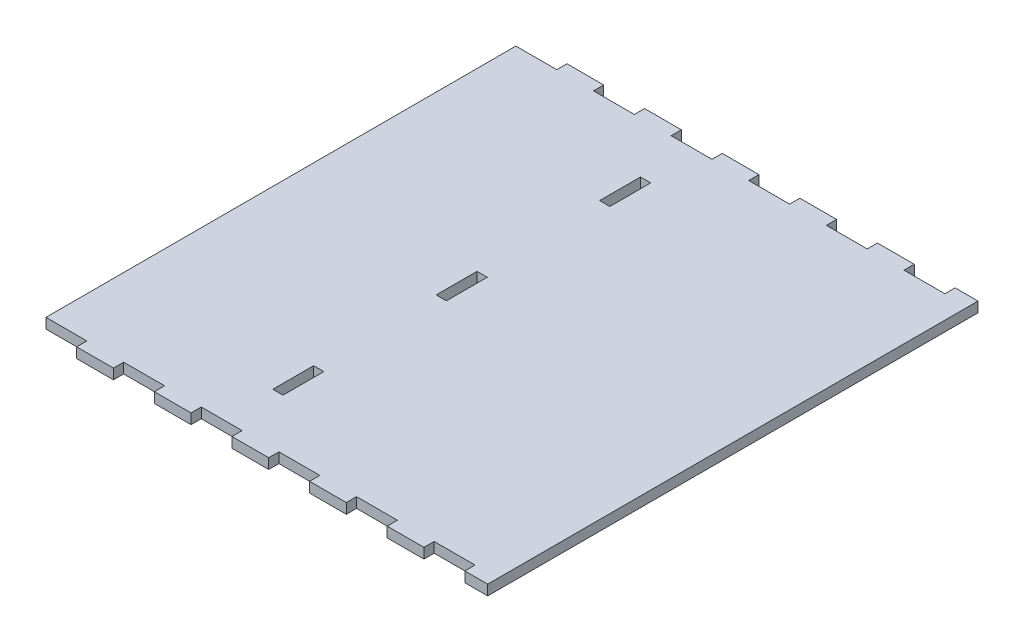
SolidWorks part; units mm, degrees
ref_plane "Front Plane" through (0, 0, 0) normal (0, 0, 1) x (1, 0, 0)
ref_plane "Top Plane" through (0, 0, 0) normal (0, 1, 0) x (1, 0, 0)
ref_plane "Right Plane" through (0, 0, 0) normal (1, 0, 0) x (0, 0, -1)
sketch "Sketch1" plane through (0, 0, 0) normal (0, 1, 0) x (1, 0, 0)
  line L76 (-42.7989, -43.0029) -> (-19.9389, -43.0029)
  line L77 (-19.9389, -43.0029) -> (-19.9389, -36.6529)
  line L78 (-19.9389, -36.6529) -> (5.4611, -36.6529)
  line L79 (5.4611, -36.6529) -> (5.4611, -43.0029)
  line L80 (5.4611, -43.0029) -> (28.3211, -43.0029)
  line L81 (28.3211, -43.0029) -> (28.3211, -36.6529)
  line L82 (28.3211, -36.6529) -> (53.7211, -36.6529)
  line L83 (53.7211, -36.6529) -> (53.7211, -43.0029)
  line L84 (53.7211, -43.0029) -> (76.5811, -43.0029)
  line L85 (76.5811, -43.0029) -> (76.5811, -36.6529)
  line L86 (76.5811, -36.6529) -> (101.9811, -36.6529)
  line L87 (101.9811, -36.6529) -> (101.9811, -43.0029)
  line L88 (101.9811, -43.0029) -> (124.8411, -43.0029)
  line L89 (124.8411, -43.0029) -> (124.8411, -36.6529)
  line L90 (124.8411, -36.6529) -> (150.2411, -36.6529)
  line L91 (150.2411, -36.6529) -> (150.2411, -43.0029)
  line L92 (150.2411, -43.0029) -> (173.1011, -43.0029)
  line L93 (173.1011, -43.0029) -> (173.1011, -36.6529)
  line L94 (173.1011, -36.6529) -> (198.5011, -36.6529)
  line L95 (198.5011, -36.6529) -> (198.5011, -43.0029)
  line L96 (198.5011, -43.0029) -> (212.7251, -43.0029)
  line L97 (-42.7989, 261.7971) -> (-19.9389, 261.7971)
  line L98 (-19.9389, 261.7971) -> (-19.9389, 255.4471)
  line L99 (-19.9389, 255.4471) -> (5.4611, 255.4471)
  line L100 (5.4611, 255.4471) -> (5.4611, 261.7971)
  line L101 (5.4611, 261.7971) -> (28.3211, 261.7971)
  line L102 (28.3211, 261.7971) -> (28.3211, 255.4471)
  line L103 (28.3211, 255.4471) -> (53.7211, 255.4471)
  line L104 (53.7211, 255.4471) -> (53.7211, 261.7971)
  line L105 (53.7211, 261.7971) -> (76.5811, 261.7971)
  line L106 (76.5811, 261.7971) -> (76.5811, 255.4471)
  line L107 (76.5811, 255.4471) -> (101.9811, 255.4471)
  line L108 (101.9811, 255.4471) -> (101.9811, 261.7971)
  line L109 (101.9811, 261.7971) -> (124.8411, 261.7971)
  line L110 (124.8411, 261.7971) -> (124.8411, 255.4471)
  line L111 (124.8411, 255.4471) -> (150.2411, 255.4471)
  line L112 (150.2411, 255.4471) -> (150.2411, 261.7971)
  line L113 (150.2411, 261.7971) -> (173.1011, 261.7971)
  line L114 (173.1011, 261.7971) -> (173.1011, 255.4471)
  line L115 (173.1011, 255.4471) -> (198.5011, 255.4471)
  line L116 (198.5011, 255.4471) -> (198.5011, 261.7971)
  line L117 (198.5011, 261.7971) -> (212.7251, 261.7971)
  line L118 (212.7251, -43.0029) -> (212.7251, 261.7971)
  line L119 (-42.7989, 261.7971) -> (-42.7989, 255.4471)
  line L120 (-42.7989, 255.4471) -> (-68.1989, 255.4471)
  line L123 (-42.7989, -43.0029) -> (-42.7989, -36.6529)
  line L124 (-42.7989, -36.6529) -> (-68.1989, -36.6529)
  line L128 (-68.1989, 255.4471) -> (-68.1989, -36.6529)
  dimension "D2" = 304.8
  dimension "D3" = 25.4
  dimension "D4" = 22.86
  dimension "D5" = 14.224
  dimension "D6" = 25.4
  dimension "D7" = 22.86
  dimension "D8" = 14.224
  dimension "D9" = 6.35
  dimension "D10" = 6.35
  dimension "D11" = 22.86
  dimension "D12" = 22.86
  dimension "D13" = 25.4
  dimension "D15" = 25.4
extrude "Boss-Extrude1" add sketch "Sketch1" along normal blind 6.35
sketch "Sketch2" plane through (0, 6.35, 0) normal (0, 1, 0) x (1, 0, 0)
  line L0 (53.7211, 255.4471) -> (28.3211, 255.4471) construction
  line L1 (41.0211, 223.6971) -> (47.3711, 223.6971)
  line L2 (41.0211, 223.6971) -> (41.0211, 198.2971)
  line L3 (41.0211, 198.2971) -> (47.3711, 198.2971)
  line L4 (47.3711, 223.6971) -> (47.3711, 198.2971)
  line L5 (41.0211, 20.4971) -> (47.3711, 20.4971)
  line L6 (41.0211, 20.4971) -> (41.0211, -4.9029)
  line L7 (41.0211, -4.9029) -> (47.3711, -4.9029)
  line L8 (47.3711, 20.4971) -> (47.3711, -4.9029)
  line L9 (41.0211, 122.0971) -> (47.3711, 122.0971)
  line L10 (41.0211, 122.0971) -> (41.0211, 96.6971)
  line L11 (-19.9389, 261.7971) -> (-42.7989, 261.7971) construction
  line L12 (-42.7989, -43.0029) -> (-19.9389, -43.0029) construction
  line L13 (-68.1989, 255.4471) -> (-68.1989, -36.6529) construction
  line L14 (41.0211, 96.6971) -> (47.3711, 96.6971)
  line L15 (47.3711, 122.0971) -> (47.3711, 96.6971)
  dimension "D7" = 25.4
  dimension "D1" = 6.35
  dimension "D2" = 25.4
  dimension "D3" = 38.1
  dimension "D4" = 38.1
  dimension "D5" = 109.22
  dimension "D6" = 109.22
  dimension "D8" = 6.35
  dimension "D9" = 133.35
extrude "Cut-Extrude1" cut sketch "Sketch2" against normal through all
